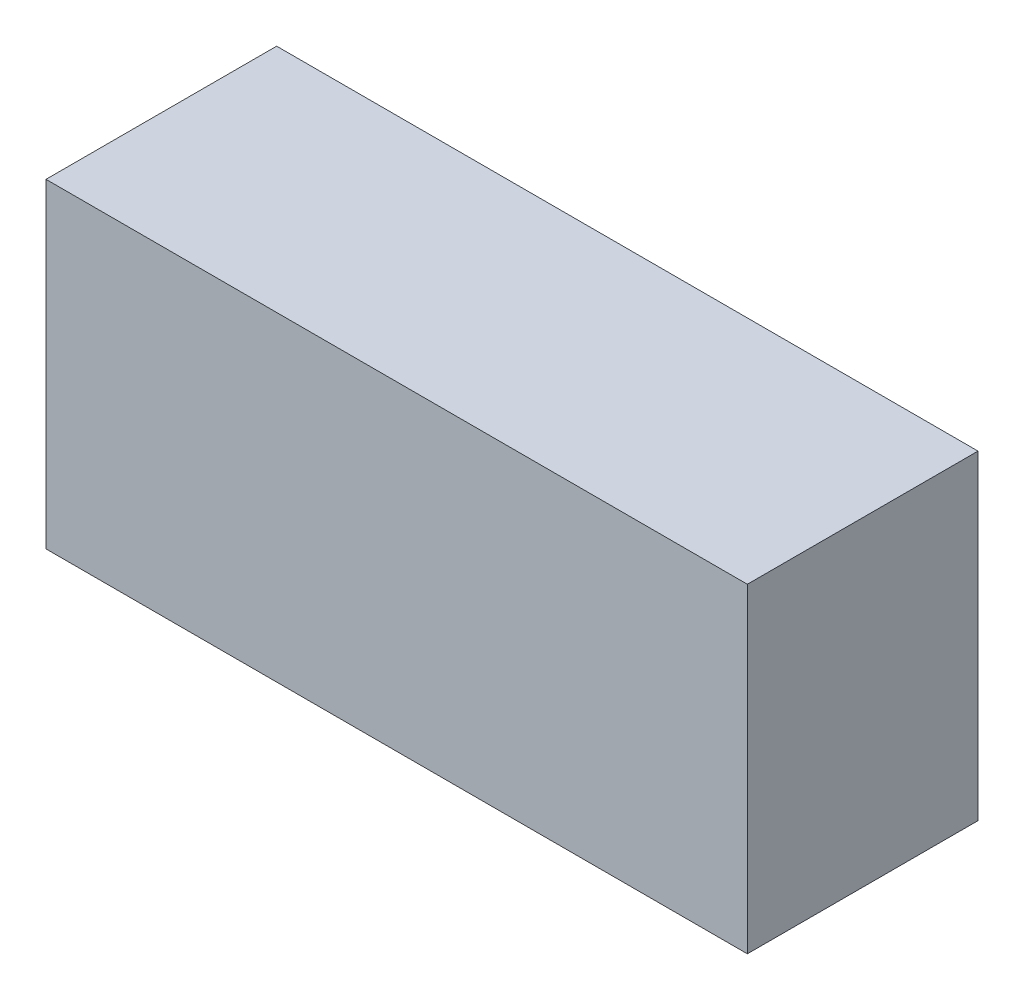
SolidWorks part; units mm, degrees
material "Battery"
ref_plane "Front Plane" through (0, 0, 0) normal (0, 0, 1) x (1, 0, 0)
ref_plane "Top Plane" through (0, 0, 0) normal (0, 1, 0) x (1, 0, 0)
ref_plane "Right Plane" through (0, 0, 0) normal (1, 0, 0) x (0, 0, -1)
sketch "Sketch1" plane through (0, 0, 0) normal (0, 1, 0) x (1, 0, 0)
  line L0 (0, 12.25) -> (0, -12.25) construction
  line L1 (-37.25, 12.25) -> (37.25, 12.25)
  line L2 (-37.25, 12.25) -> (-37.25, -12.25)
  line L3 (-37.25, -12.25) -> (37.25, -12.25)
  line L4 (37.25, 12.25) -> (37.25, -12.25)
  point P6 (0, 0)
  dimension "D1" = 74.5
  dimension "D2" = 24.5
extrude "Boss-Extrude1" add sketch "Sketch1" along normal blind 34
sketch "Sketch2" plane through (-37.25, 0, 0) normal (-1, 0, 0) x (0, 0, 1)
  line L0 (-12.25, 34) -> (12.25, 34) construction
  line L1 (-12.25, 34) -> (-12.25, 0) construction
  circle A0 centre (-7.25, 31.5) radius 2.5
  circle A1 centre (-1.75, 31.5) radius 2.5
  dimension "D1" = 5
  dimension "D4" = 5
  dimension "D2" = 2.5
  dimension "D3" = 5
  dimension "D5" = 5.5
  dimension "D6" = 2.5
extrude "Boss-Extrude2" [suppressed] add sketch "Sketch2" along normal blind 70
sketch "Sketch3" [suppressed] plane through (-107.25, 0, 0) normal (-1, 0, 0) x (0, 0, 1)
  line L5 (-12.25, 34) -> (-7.25, 34) construction
  line L7 (-9.75, 34) -> (0.75, 34)
  line L8 (-9.75, 34) -> (-9.75, 29)
  line L9 (-9.75, 29) -> (0.75, 29)
  line L10 (0.75, 34) -> (0.75, 29)
  circle A0 centre (-1.75, 31.5) radius 2.5 construction
  circle A3 centre (-1.75, 31.5) radius 2.5 construction
  dimension "D1" = 2.5
  dimension "D2" = 2.5
extrude "Boss-Extrude3" [suppressed] add sketch "Sketch3" along normal blind 20
